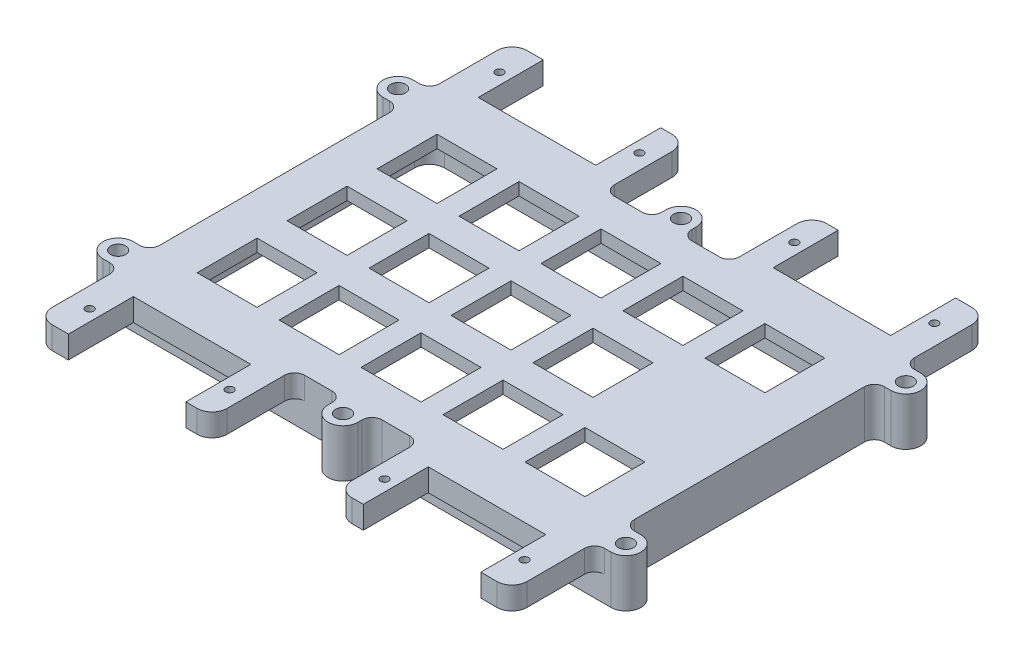
SolidWorks part; units mm, degrees
ref_plane "前视基准面" through (0, 0, 0) normal (0, 0, 1) x (1, 0, 0)
ref_plane "上视基准面" through (0, 0, 0) normal (0, 1, 0) x (1, 0, 0)
ref_plane "右视基准面" through (0, 0, 0) normal (1, 0, 0) x (0, 0, -1)
other "Configuration Table"
sketch "草图1" plane through (0, 0, 0) normal (0, 1, 0) x (1, 0, 0)
  line L0 (0, 35.4779) -> (0, -35.3561) construction
  line L2 (-47.5, 23) -> (-47.5, -23)
  line L4 (47.5, 23) -> (47.5, -23)
  line L5 (-47.5, 31) -> (47.5, -31) construction
  line L6 (-47.5, -31) -> (47.5, 31) construction
  line L15 (-78.7463, 0) -> (58.6748, 0) construction
  line L24 (-10.5, 31) -> (-5, 31)
  line L27 (-10.5, -31) -> (-5, -31)
  line L28 (49.5, 31) -> (50.8, 31)
  line L29 (-49.5, 31) -> (-50.8, 31)
  line L31 (-49.5, 25) -> (-50.8, 25)
  line L33 (49.5, 25) -> (50.8, 25)
  line L36 (49.5, -25) -> (50.8, -25)
  line L37 (49.5, -31) -> (50.8, -31)
  line L38 (-49.5, -31) -> (-50.8, -31)
  line L39 (-49.5, -25) -> (-50.8, -25)
  line L41 (-3, -33.8) -> (-3, -33)
  line L43 (-3, 33.8) -> (-3, 33)
  line L45 (3, 33.8) -> (3, 33)
  line L47 (3, -33.8) -> (3, -33)
  line L48 (5, 31) -> (10.5, 31)
  line L49 (5, -31) -> (10.5, -31)
  line L54 (29.5, 63.8424) -> (29.5, 47.5) construction
  line L56 (47.5, 33) -> (47.5, 44.5)
  line L57 (44.5, 47.5) -> (41.25, 47.5)
  line L58 (12.5, 33) -> (12.5, 44.5)
  line L59 (17.75, 47.5) -> (15.5, 47.5)
  line L60 (17.75, 34.5) -> (41.25, 34.5)
  line L61 (17.75, 34.5) -> (17.75, 47.5)
  line L63 (41.25, 34.5) -> (41.25, 47.5)
  line L65 (12.5, -33) -> (12.5, -44.5)
  line L66 (29.5, 34.5) -> (29.5, 25) construction
  line L67 (17.75, -47.5) -> (15.5, -47.5)
  line L68 (17.75, -34.5) -> (17.75, -47.5)
  line L69 (17.75, -34.5) -> (41.25, -34.5)
  line L70 (41.25, -34.5) -> (41.25, -47.5)
  line L71 (44.5, -47.5) -> (41.25, -47.5)
  line L72 (47.5, -33) -> (47.5, -44.5)
  line L73 (-47.5, -33) -> (-47.5, -44.5)
  line L74 (-44.5, -47.5) -> (-41.25, -47.5)
  line L75 (-41.25, -34.5) -> (-41.25, -47.5)
  line L76 (-17.75, -34.5) -> (-41.25, -34.5)
  line L77 (-17.75, -34.5) -> (-17.75, -47.5)
  line L78 (-17.75, -47.5) -> (-15.5, -47.5)
  line L79 (-12.5, -33) -> (-12.5, -44.5)
  line L82 (-12.5, 33) -> (-12.5, 44.5)
  line L83 (-17.75, 47.5) -> (-15.5, 47.5)
  line L84 (-17.75, 34.5) -> (-17.75, 47.5)
  line L85 (-17.75, 34.5) -> (-41.25, 34.5)
  line L86 (-41.25, 34.5) -> (-41.25, 47.5)
  line L87 (-44.5, 47.5) -> (-41.25, 47.5)
  line L88 (-47.5, 33) -> (-47.5, 44.5)
  arc A4 (-50.8, 31) -> (-50.8, 25) centre (-50.8, 28) ccw
  circle A5 centre (-50.8, 28) radius 1.5
  circle A6 centre (50.8, 28) radius 1.5
  arc A7 (50.8, 31) -> (50.8, 25) centre (50.8, 28) cw
  circle A8 centre (50.8, -28) radius 1.5
  arc A9 (50.8, -31) -> (50.8, -25) centre (50.8, -28) ccw
  circle A10 centre (-50.8, -28) radius 1.5
  arc A11 (-50.8, -31) -> (-50.8, -25) centre (-50.8, -28) cw
  arc A12 (-3, 33.8) -> (3, 33.8) centre (0, 33.8) cw
  circle A13 centre (0, 33.8) radius 1.5
  circle A14 centre (0, -33.8) radius 1.5
  arc A15 (-3, -33.8) -> (3, -33.8) centre (0, -33.8) ccw
  arc A16 (47.5, 44.5) -> (44.5, 47.5) centre (44.5, 44.5) ccw
  arc A17 (15.5, 47.5) -> (12.5, 44.5) centre (15.5, 44.5) ccw
  circle A18 centre (43.5, 41) radius 0.8
  circle A19 centre (15.5, 41) radius 0.8
  circle A20 centre (43.5, -41) radius 0.8
  circle A21 centre (15.5, -41) radius 0.8
  arc A22 (15.5, -47.5) -> (12.5, -44.5) centre (15.5, -44.5) cw
  arc A23 (47.5, -44.5) -> (44.5, -47.5) centre (44.5, -44.5) cw
  circle A24 centre (-15.5, -41) radius 0.8
  circle A25 centre (-43.5, -41) radius 0.8
  arc A26 (-47.5, -44.5) -> (-44.5, -47.5) centre (-44.5, -44.5) ccw
  arc A27 (-15.5, -47.5) -> (-12.5, -44.5) centre (-15.5, -44.5) ccw
  circle A28 centre (-43.5, 41) radius 0.8
  circle A29 centre (-15.5, 41) radius 0.8
  arc A30 (-15.5, 47.5) -> (-12.5, 44.5) centre (-15.5, 44.5) cw
  arc A31 (-47.5, 44.5) -> (-44.5, 47.5) centre (-44.5, 44.5) cw
  arc A32 (47.5, -23) -> (49.5, -25) centre (49.5, -23) ccw
  arc A33 (49.5, 25) -> (47.5, 23) centre (49.5, 23) ccw
  arc A34 (-49.5, -25) -> (-47.5, -23) centre (-49.5, -23) ccw
  arc A35 (-47.5, 23) -> (-49.5, 25) centre (-49.5, 23) ccw
  arc A36 (-49.5, -31) -> (-47.5, -33) centre (-49.5, -33) cw
  arc A37 (-12.5, -33) -> (-10.5, -31) centre (-10.5, -33) cw
  arc A38 (-3, -33) -> (-5, -31) centre (-5, -33) ccw
  arc A39 (5, -31) -> (3, -33) centre (5, -33) ccw
  arc A40 (10.5, -31) -> (12.5, -33) centre (10.5, -33) cw
  arc A41 (47.5, -33) -> (49.5, -31) centre (49.5, -33) cw
  arc A42 (47.5, 33) -> (49.5, 31) centre (49.5, 33) ccw
  arc A43 (10.5, 31) -> (12.5, 33) centre (10.5, 33) ccw
  arc A44 (5, 31) -> (3, 33) centre (5, 33) cw
  arc A45 (-3, 33) -> (-5, 31) centre (-5, 33) cw
  arc A46 (-10.5, 31) -> (-12.5, 33) centre (-10.5, 33) cw
  arc A47 (-47.5, 33) -> (-49.5, 31) centre (-49.5, 33) cw
  point P0 (0, 0)
  point P14 (47.5, -25)
  point P21 (29.5, 41)
  point P24 (47.5, 25)
  point P62 (47.5, 47.5)
  point P65 (12.5, 47.5)
  point P117 (-47.5, -25)
  point P120 (-47.5, 25)
  point P126 (-12.5, -31)
  point P129 (-3, -31)
  point P132 (3, -31)
  point P135 (12.5, -31)
  point P144 (12.5, 31)
  point P147 (3, 31)
  point P150 (-3, 31)
  point P153 (-12.5, 31)
  dimension "D8" = 2.8
  dimension "D11" = 3
  dimension "D12" = 6.5
  dimension "D3" = 2
  dimension "D1" = 95
  dimension "D2" = 62
  dimension "D4" = 35
  dimension "D5" = 23.5
  dimension "D6" = 3.3
  dimension "D7" = 6
  dimension "D9" = 6
  dimension "D13" = 2.25
extrude "凸台-拉伸1" add sketch "草图1" against normal blind 9.6
sketch "草图2" plane through (0, -9.6, 0) normal (0, -1, 0) x (1, 0, 0)
  line L0 (-63.1336, 0) -> (63.5579, 0) construction
  line L5 (0, 56.9992) -> (0, 48.5806) construction
  line L18 (3, 33.8) -> (3, 33) construction
  line L19 (63.5579, 31) -> (5, 31)
  line L20 (63.5579, 31) -> (63.5579, 53.6942)
  line L21 (63.5579, 53.6942) -> (-73.0103, 53.6942)
  line L22 (-73.0103, 31) -> (-73.0103, 53.6942)
  line L23 (-3, 33) -> (-3, 33.8) construction
  line L24 (3, 33.8) -> (3, 33)
  line L25 (-3, 33) -> (-3, 33.8)
  line L26 (-5, 31) -> (-73.0103, 31)
  line L27 (63.5579, -31) -> (63.5579, -53.6942)
  line L28 (63.5579, -53.6942) -> (-73.0103, -53.6942)
  line L29 (-73.0103, -31) -> (-73.0103, -53.6942)
  line L30 (-5, -31) -> (-73.0103, -31)
  line L31 (-3, -33) -> (-3, -33.8)
  line L32 (3, -33.8) -> (3, -33)
  line L33 (63.5579, -31) -> (5, -31)
  arc A3 (3, 33) -> (5, 31) centre (5, 33) ccw construction
  arc A4 (3, 33.8) -> (-3, 33.8) centre (0, 33.8) ccw construction
  arc A5 (-5, 31) -> (-3, 33) centre (-5, 33) ccw construction
  arc A6 (3, 33) -> (5, 31) centre (5, 33) ccw
  arc A7 (3, 33.8) -> (-3, 33.8) centre (0, 33.8) ccw
  arc A8 (-5, 31) -> (-3, 33) centre (-5, 33) ccw
  arc A9 (-5, -31) -> (-3, -33) centre (-5, -33) cw
  arc A10 (3, -33.8) -> (-3, -33.8) centre (0, -33.8) cw
  arc A11 (3, -33) -> (5, -31) centre (5, -33) cw
extrude "切除-拉伸1" cut sketch "草图2" against normal blind 5.1
sketch "草图3" plane through (0, -9.6, 0) normal (0, -1, 0) x (1, 0, 0)
  line L0 (47.5, 23) -> (47.5, -23) construction
  line L1 (-45, -28.5) -> (45, -28.5)
  line L2 (-45, -28.5) -> (-45, 28.5)
  line L3 (-45, 28.5) -> (45, 28.5)
  line L4 (45, -28.5) -> (45, 28.5)
  line L5 (-45, -28.5) -> (45, 28.5) construction
  line L6 (-45, 28.5) -> (45, -28.5) construction
  line L7 (-50.8, 31) -> (-5, 31) construction
  point P0 (0, 0)
  dimension "D1" = 2.5
  dimension "D2" = 2.5
extrude "切除-拉伸2" cut sketch "草图3" against normal blind 7.1
fillet "圆角1" radius 3 4 edges at (-45, -6.05, -28.5) (-45, -6.05, 28.5) (45, -6.05, -28.5) (45, -6.05, 28.5)
sketch "草图11" plane through (0, -2.5, 0) normal (0, -1, 0) x (1, 0, 0)
  line L0 (0, 44.5522) -> (0, -50.2123) construction
  line L1 (-64.7486, 0) -> (58.5739, 0) construction
  line L2 (42, 28.5) -> (-42, 28.5) construction
  line L3 (-30, 17) -> (30, 17)
  line L4 (-30, 17) -> (-30, 19.5)
  line L5 (-30, 19.5) -> (-1.5, 19.5)
  line L6 (30, 17) -> (30, 19.5)
  line L7 (-30, 17) -> (30, 19.5) construction
  line L8 (-30, 19.5) -> (30, 17) construction
  line L9 (1.5, 19.5) -> (30, 19.5)
  line L10 (-1.5, 28.5) -> (1.5, 28.5)
  line L11 (-1.5, 28.5) -> (-1.5, 19.5)
  line L13 (1.5, 28.5) -> (1.5, 19.5)
  line L14 (1.5, -28.5) -> (1.5, -19.5)
  line L15 (-1.5, -28.5) -> (1.5, -28.5)
  line L16 (-1.5, -28.5) -> (-1.5, -19.5)
  line L17 (-30, -19.5) -> (-1.5, -19.5)
  line L18 (-30, -17) -> (-30, -19.5)
  line L19 (-30, -17) -> (30, -17)
  line L20 (30, -17) -> (30, -19.5)
  line L21 (1.5, -19.5) -> (30, -19.5)
  point P5 (0, 18.25)
  dimension "D1" = 60
  dimension "D2" = 2.5
  dimension "D3" = 9
  dimension "D4" = 3
extrude "凸台-拉伸2" [suppressed] add sketch "草图11" along normal blind 2
sketch "草图12" plane through (0, -2.5, 0) normal (0, -1, 0) x (1, 0, 0)
  line L0 (0, 44.2091) -> (0, -42.6655) construction
  line L1 (-42, 25.5) -> (-7, 25.5)
  line L2 (-42, 25.5) -> (-42, 23)
  line L3 (-42, 23) -> (-7, 23)
  line L4 (-7, 25.5) -> (-7, 23)
  line L5 (-53.0853, 0) -> (71.5236, 0) construction
  line L6 (42, 23) -> (7, 23)
  line L7 (7, 25.5) -> (7, 23)
  line L8 (42, 25.5) -> (7, 25.5)
  line L9 (42, 25.5) -> (42, 23)
  line L10 (42, -25.5) -> (42, -23)
  line L11 (42, -25.5) -> (7, -25.5)
  line L12 (7, -25.5) -> (7, -23)
  line L13 (42, -23) -> (7, -23)
  line L14 (-42, -23) -> (-7, -23)
  line L15 (-7, -25.5) -> (-7, -23)
  line L16 (-42, -25.5) -> (-7, -25.5)
  line L17 (-42, -25.5) -> (-42, -23)
  dimension "D1" = 35
  dimension "D2" = 2.5
fillet "圆角2" radius 1 8 edges at (0, -2.5, -28.5) (-44.1213, -2.5, -27.6213) (-45, -2.5, 0) (-44.1213, -2.5, 27.6213) (0, -2.5, 28.5) (44.1213, -2.5, 27.6213) (45, -2.5, 0) (44.1213, -2.5, -27.6213)
sketch "草图13" plane through (0, -2.5, 0) normal (0, -1, 0) x (1, 0, 0)
  line L0 (-56.0869, 0) -> (61.3182, 0) construction
  line L1 (0, 42.7512) -> (0, -42.4082) construction
  line L2 (-45, -25.5) -> (-45, 25.5) construction
  line L3 (-39, 24) -> (-27, 24)
  line L4 (-39, 24) -> (-39, 12)
  line L5 (-39, 12) -> (-27, 12)
  line L6 (-27, 24) -> (-27, 12)
  line L7 (-39, 24) -> (-27, 12) construction
  line L8 (-39, 12) -> (-27, 24) construction
  line L9 (-22.6, 24) -> (-22.6, 12)
  line L10 (-22.6, 24) -> (-10.6, 24)
  line L11 (-10.6, 24) -> (-10.6, 12)
  line L12 (-22.6, 12) -> (-10.6, 12)
  line L13 (-6.2, 24) -> (-6.2, 12)
  line L14 (-6.2, 24) -> (5.8, 24)
  line L15 (5.8, 24) -> (5.8, 12)
  line L16 (-6.2, 12) -> (5.8, 12)
  line L17 (10.2, 24) -> (10.2, 12)
  line L18 (10.2, 24) -> (22.2, 24)
  line L19 (22.2, 24) -> (22.2, 12)
  line L20 (10.2, 12) -> (22.2, 12)
  line L21 (26.6, 24) -> (26.6, 12)
  line L22 (26.6, 24) -> (38.6, 24)
  line L23 (38.6, 24) -> (38.6, 12)
  line L24 (26.6, 12) -> (38.6, 12)
  line L25 (-22.6, 6) -> (-22.6, -6)
  line L26 (-22.6, 6) -> (-10.6, 6)
  line L27 (-10.6, 6) -> (-10.6, -6)
  line L28 (-22.6, -6) -> (-10.6, -6)
  line L29 (-6.2, 6) -> (-6.2, -6)
  line L30 (-6.2, 6) -> (5.8, 6)
  line L31 (5.8, 6) -> (5.8, -6)
  line L32 (-6.2, -6) -> (5.8, -6)
  line L33 (10.2, 6) -> (10.2, -6)
  line L34 (10.2, 6) -> (22.2, 6)
  line L35 (22.2, 6) -> (22.2, -6)
  line L36 (10.2, -6) -> (22.2, -6)
  line L41 (-22.6, -12) -> (-22.6, -24)
  line L42 (-22.6, -12) -> (-10.6, -12)
  line L43 (-10.6, -12) -> (-10.6, -24)
  line L44 (-22.6, -24) -> (-10.6, -24)
  line L45 (-6.2, -12) -> (-6.2, -24)
  line L46 (-6.2, -12) -> (5.8, -12)
  line L47 (5.8, -12) -> (5.8, -24)
  line L48 (-6.2, -24) -> (5.8, -24)
  line L49 (10.2, -12) -> (10.2, -24)
  line L50 (10.2, -12) -> (22.2, -12)
  line L51 (22.2, -12) -> (22.2, -24)
  line L52 (10.2, -24) -> (22.2, -24)
  line L53 (26.6, -12) -> (26.6, -24)
  line L54 (26.6, -12) -> (38.6, -12)
  line L55 (38.6, -12) -> (38.6, -24)
  line L56 (26.6, -24) -> (38.6, -24)
  line L57 (-39, 6) -> (-39, -6)
  line L58 (-39, 6) -> (-27, 6)
  line L59 (-27, 6) -> (-27, -6)
  line L60 (-39, -6) -> (-27, -6)
  line L61 (-39, -12) -> (-39, -24)
  line L62 (-39, -12) -> (-27, -12)
  line L63 (-27, -12) -> (-27, -24)
  line L64 (-39, -24) -> (-27, -24)
  line L65 (26.6, 6) -> (38.6, 6) [skipped]
  line L66 (26.6, 0) -> (26.6, -6) [skipped]
  line L67 (26.6, -6) -> (38.6, -6) [skipped]
  line L68 (38.6, 6) -> (38.6, 0) [skipped]
  point P5 (-33, 18)
  dimension "D1" = 12
  dimension "D2" = 12
  dimension "D3" = 18
  dimension "D4" = 12
  dimension "D5" = 5
  dimension "D6" = 3
extrude "切除-拉伸3" cut sketch "草图13" against normal through all
